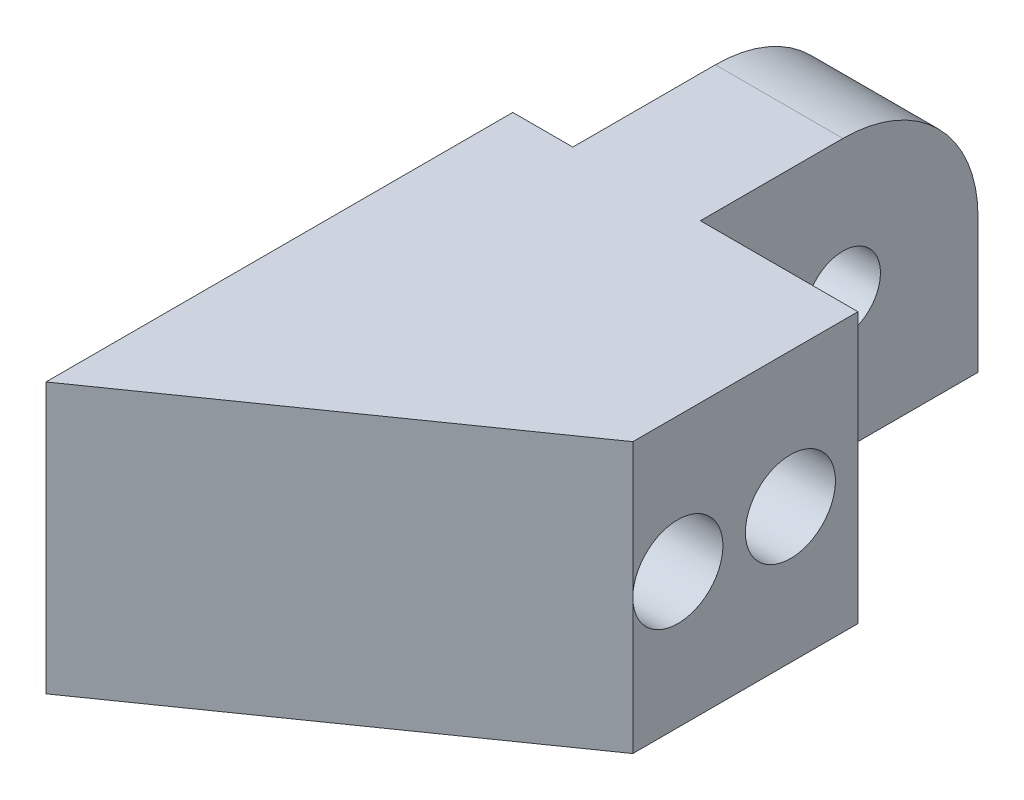
SolidWorks part; units mm, degrees
ref_plane "Front Plane" through (0, 0, 0) normal (0, 0, 1) x (1, 0, 0)
ref_plane "Top Plane" through (0, 0, 0) normal (0, 1, 0) x (1, 0, 0)
ref_plane "Right Plane" through (0, 0, 0) normal (1, 0, 0) x (0, 0, -1)
sketch "Sketch1" plane through (0, 0, 0) normal (0, 1, 0) x (1, 0, 0)
  line L0 (-8.25, 7.5) -> (-8.25, -23.6048)
  line L1 (-8.25, -23.6048) -> (14.75, -7.5)
  line L2 (14.75, -7.5) -> (14.75, 7.5)
  line L3 (14.75, 7.5) -> (4.25, 7.5)
  line L4 (4.25, 7.5) -> (4.25, 26)
  line L5 (4.25, 26) -> (-4.25, 26)
  line L6 (-4.25, 26) -> (-4.25, 7.5)
  line L7 (-4.25, 7.5) -> (-8.25, 7.5)
  line L8 (-8.25, 0) -> (14.75, 0) construction
  line L9 (0, 26) -> (0, -17.8281) construction
  dimension "D1" = 10.5
  dimension "D2" = 4
  dimension "D3" = 8.5
  dimension "D4" = 18.5
  dimension "D5" = 15
  dimension "D6" = 55
extrude "Boss-Extrude1" add sketch "Sketch1" along normal blind 18
sketch "Sketch3" plane through (-8.25, 0, 0) normal (-1, 0, 0) x (0, 0, 1)
  line L0 (-17, 18) -> (-17, 0) construction
  line L1 (-26, 9) -> (-26, 18)
  line L2 (-26, 18) -> (-17, 18)
  line L3 (-26, 18) -> (-7.5, 18) construction
  line L5 (-26, 18) -> (-26, 0) construction
  line L6 (-26, 9) -> (23.6048, 9) construction
  line L7 (23.6048, 18) -> (23.6048, 0) construction
  line L8 (-7.5, 18) -> (-7.5, 0) construction
  arc A0 (-17, 18) -> (-26, 9) centre (-17, 9) ccw
  circle A1 centre (-17, 9) radius 2.5
  circle A2 centre (-3, 9) radius 3
  circle A3 centre (4.5, 9) radius 3
  point P2 (-17, 9)
  point P13 (-3, 9)
  point P14 (4.5, 9)
  dimension "D4" = 6
  dimension "D5" = 5
  dimension "D1" = 9
  dimension "D2" = 4.5
  dimension "D3" = 7.5
extrude "Cut-Extrude1" cut sketch "Sketch3" against normal through all
